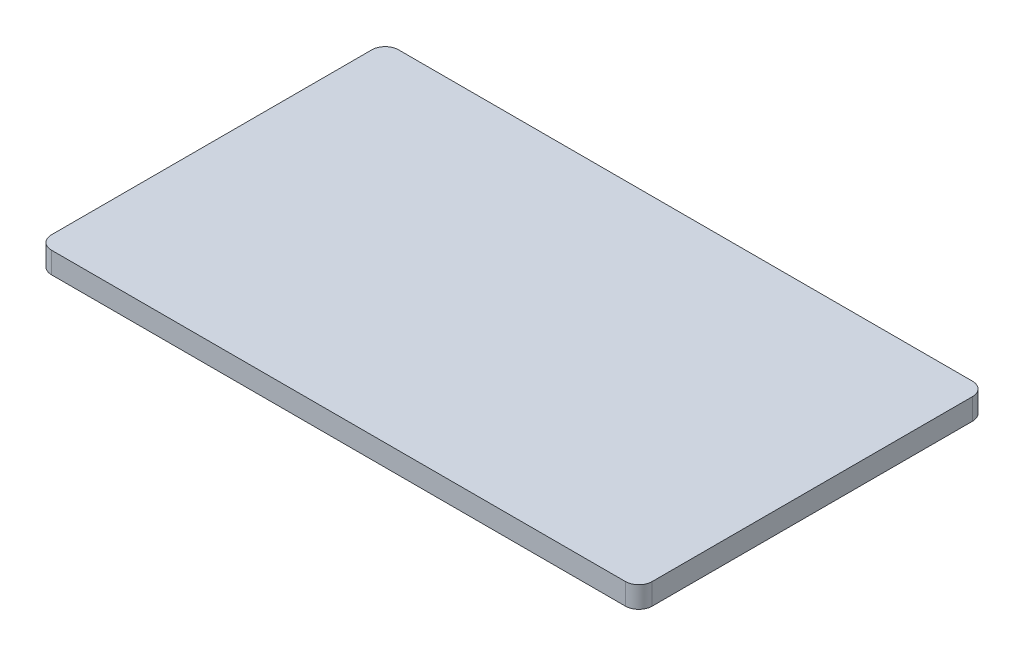
SolidWorks part; units mm, degrees
ref_plane "Front" through (0, 0, 0) normal (0, 0, 1) x (1, 0, 0)
ref_plane "Top" through (0, 0, 0) normal (0, 1, 0) x (1, 0, 0)
ref_plane "Right" through (0, 0, 0) normal (1, 0, 0) x (0, 0, -1)
sketch "Sketch1" plane through (0, 0, 0) normal (0, 1, 0) x (1, 0, 0)
  line L1 (-22.5, -13) -> (22.5, -13)
  line L2 (-22.5, -13) -> (-22.5, 13)
  line L3 (-22.5, 13) -> (22.5, 13)
  line L4 (22.5, -13) -> (22.5, 13)
  line L5 (-22.5, -13) -> (22.5, 13) construction
  line L6 (-22.5, 13) -> (22.5, -13) construction
  point P0 (0, 0)
  dimension "D1" = 45
  dimension "D2" = 26
extrude "Boss-Extrude1" add sketch "Sketch1" along normal blind 1.6
fillet "Fillet1" radius 1 4 edges at (22.5, 0.8, 13) (22.5, 0.8, -13) (-22.5, 0.8, -13) (-22.5, 0.8, 13)
